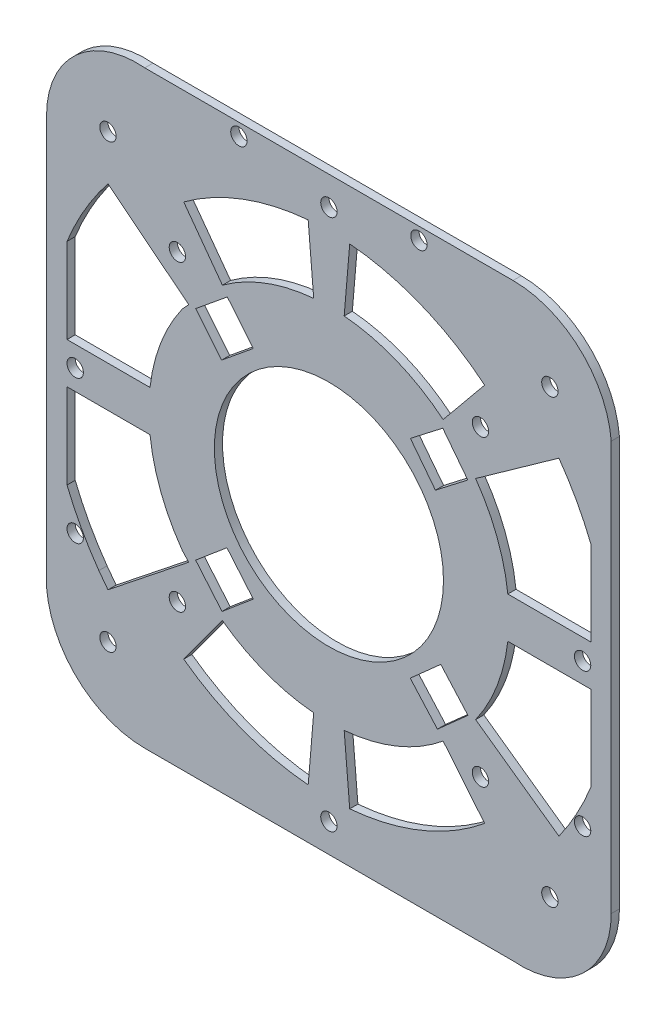
SolidWorks part; units mm, degrees
ref_plane "Front Plane" through (0, 0, 0) normal (0, 0, 1) x (1, 0, 0)
ref_plane "Top Plane" through (0, 0, 0) normal (0, 1, 0) x (1, 0, 0)
ref_plane "Right Plane" through (0, 0, 0) normal (1, 0, 0) x (0, 0, -1)
sketch "Sketch1" plane through (0, 0, 0) normal (0, 0, 1) x (1, 0, 0)
  line L1 (69, -50) -> (-69, -50)
  line L2 (69, -50) -> (69, 50)
  line L3 (69, 50) -> (-69, 50)
  line L4 (-69, -50) -> (-69, 50)
  line L5 (69, -50) -> (-69, 50) construction
  line L6 (69, 50) -> (-69, -50) construction
  line L7 (45, -72) -> (-45, -72)
  line L8 (45, -72) -> (45, 72)
  line L9 (45, 72) -> (-45, 72)
  line L10 (-45, -72) -> (-45, 72)
  line L11 (45, -72) -> (-45, 72) construction
  line L12 (45, 72) -> (-45, -72) construction
  arc A0 (-69, 50) -> (-45, 72) centre (-46.9167, 50) cw
  arc A1 (45, 72) -> (69, 50) centre (45, 47.9091) cw
  arc A2 (69, -50) -> (45, -72) centre (46.9167, -50) cw
  arc A3 (-45, -72) -> (-69, -50) centre (-45, -47.9091) cw
  point P0 (0, 0)
  point P6 (0, 0)
extrude "Boss-Extrude1" add sketch "Sketch1" along normal blind 2 contours L10 L1 L8 L3 | L10 L3 L8 L9 | L8 L1 L2 L3 | A1 L8 L3 | A2 L1 L8 | L10 L7 L8 L1 | A3 L10 L1 | L1 L10 L3 L4 | A0 L3 L10
sketch "Sketch2" plane through (0, 0, 2) normal (0, 0, 1) x (1, 0, 0)
  line L0 (-69, 0) -> (-64, 0)
  line L1 (69, 0) -> (64, 0)
  line L2 (-69, -50) -> (-69, 50) construction
  line L3 (64, 0) -> (64, 25.7876)
  line L4 (64, 25.7876) -> (64, -25.7876)
  line L5 (64, -25.7876) -> (-64, -25.7876)
  line L6 (-64, -25.7876) -> (-64, 25.7876)
  line L7 (-64, 25.7876) -> (64, 25.7876)
  line L8 (0, 60) -> (5.0847, 60)
  line L9 (0, 60) -> (-5.0847, 60)
  line L10 (-5.0847, 60) -> (-5.0847, 43.715)
  line L11 (-5.0847, 43.715) -> (5.0847, 43.715)
  line L12 (5.0847, 43.715) -> (5.0847, 60)
  line L13 (5.0847, 59.7842) -> (38.0593, 46.3842)
  line L14 (38.0593, 46.3842) -> (0, 0)
  line L15 (0, 0) -> (5.0847, 59.7842)
  line L16 (-5.0847, 60) -> (-35.4831, 48.3834)
  line L17 (-35.4831, 48.3834) -> (0, 0)
  line L18 (-5.0847, 60) -> (0, 0)
  line L19 (-69, 0) -> (-56.2174, 40.0076)
  line L20 (-56.2174, 40.0076) -> (0, 0)
  line L21 (0, 0) -> (-64, 0)
  line L22 (0, 72) -> (0, -72)
  line L23 (45, 72) -> (-45, 72) construction
  line L24 (45, -72) -> (-45, -72) construction
  line L25 (0, 0) -> (69, 0)
  line L26 (-69, 0) -> (-56.2174, -40.0076)
  line L27 (-56.2174, -40.0076) -> (0, 0)
  line L28 (-5.0847, -60) -> (0, 0)
  line L29 (-35.4831, -48.3834) -> (0, 0)
  line L30 (-5.0847, -60) -> (-35.4831, -48.3834)
  line L31 (38.0593, -46.3842) -> (0, 0)
  line L32 (0, 0) -> (5.0847, -59.7842)
  line L33 (5.0847, -59.7842) -> (38.0593, -46.3842)
  line L34 (56.2174, -40.0076) -> (0, 0)
  line L35 (69, 0) -> (56.2174, -40.0076)
  line L36 (64, -25.7876) -> (64, 25.7876)
  line L37 (69, 0) -> (56.2174, 40.0076)
  line L38 (56.2174, 40.0076) -> (0, 0)
  line L40 (64, 5) -> (-64, 5)
  line L41 (64, 5) -> (64, -5)
  line L42 (64, -5) -> (-64, -5)
  line L43 (-64, 5) -> (-64, -5)
  line L44 (64, 5) -> (-64, -5) construction
  line L45 (64, -5) -> (-64, 5) construction
  circle A0 centre (0, 0) radius 60
  circle A1 centre (0, 0) radius 69
  circle A2 centre (0, 0) radius 44.0097
extrude "Cut-Extrude1" cut sketch "Sketch2" against normal blind 10 contours A2 L14 L13 L12 | L13 A0 | A2 L12 L15 | A2 L18 A0 L10 | A2 L10 A0 L16 L17 | L16 A0 | L19 A1 L7 | A0 L20 L19 L7 | L20 A0 L7 | A2 L20 L7 A0 L40 | A0 L7 L19 L6 L40 | A2 L42 A0 L5 L27 | A0 L42 L6 L26 L5 | L26 L6 L5 | L5 A1 L26 | A0 L5 L26 L27 | L5 A0 L27 | A2 L32 L33 L31 | A2 L29 L30 A0 L28 | L30 A0 | L33 A0 | A0 L34 L35 L5 | L34 A0 L5 | L35 A1 L5 | L4 L35 L5 | A0 L5 L35 L36 L42 | A2 L34 L5 A0 L42 | A0 L40 L36 L37 L7 | A0 L7 L37 L38 | L7 A0 L38 | A2 L40 A0 L7 L38 | L7 A1 L37 | L37 L36 L7
sketch "Sketch3" plane through (0, 0, 2) normal (0, 0, 1) x (1, 0, 0)
  line L0 (-64, 25.7876) -> (-64, 15.6492)
  line L1 (-64, 15.6492) -> (-60.7607, 25.7876)
  line L2 (-60.7607, 25.7876) -> (-64, 25.7876)
extrude "Cut-Extrude2" cut sketch "Sketch3" against normal blind 10
sketch "Sketch4" plane through (0, 0, 0) normal (0, 0, -1) x (-1, 0, 0)
  circle A0 centre (0, 0) radius 30
extrude "Cut-Extrude3" cut sketch "Sketch4" against normal blind 10
sketch "Sketch6" plane through (0, 0, 2) normal (0, 0, 1) x (1, 0, 0)
  line L0 (-56.2174, -40.0076) -> (56.2174, -40.0076)
  line L1 (56.2174, -40.0076) -> (56.2174, 40.0076)
  line L2 (56.2174, 40.0076) -> (-56.2174, 40.0076)
  line L3 (-56.2174, 40.0076) -> (-56.2174, -40.0076)
  line L4 (27.9163, -34.0226) -> (35.8567, -25.5177)
  line L5 (-26.0267, -35.489) -> (-34.2574, -27.2582)
  line L6 (0, 0) -> (-34.2574, -27.2582)
  line L7 (-34.2574, -27.2582) -> (-53.9933, -42.9619)
  line L8 (-53.9933, -42.9619) -> (-56.2174, -40.0076)
  line L9 (-35.8567, -25.5177) -> (-34.2574, -27.2582)
  line L10 (-69, 0) -> (69, 0)
  line L11 (-35.8567, 25.5177) -> (-34.2574, 27.2582)
  line L12 (-53.9933, 42.9619) -> (-56.2174, 40.0076)
  line L13 (-34.2574, 27.2582) -> (-53.9933, 42.9619)
  circle A0 centre (0, 0) radius 69
  line M9 (-56.2174, 40.0076) -> (-35.8567, 25.5177)
  line M37 (-35.8567, -25.5177) -> (-56.2174, -40.0076)
extrude "Cut-Extrude4" cut sketch "Sketch6" against normal blind 10 contours L9 L0 L7 M37 | L11 L13 L2 M9 | L8 L7 L0 | L2 L13 L12
sketch "Sketch7" plane through (0, 0, 2) normal (0, 0, 1) x (1, 0, 0)
  line L4 (-26.2247, 19.5306) -> (-18.4877, 25.8662)
  line L5 (-34.2574, 27.2582) -> (-26.0267, 35.489)
  line L6 (-26.2247, 19.5306) -> (-32.5603, 27.2676)
  line L7 (38.0593, 46.3842) -> (27.9163, 34.0226) construction
  line L8 (27.9163, 34.0226) -> (35.8567, 25.5177)
  line L9 (-18.4877, 25.8662) -> (-24.8233, 33.6031)
  line L10 (35.8567, -25.5177) -> (27.9163, -34.0226)
  line L11 (-32.5603, 27.2676) -> (-24.8233, 33.6031)
  line L12 (-26.0267, -35.489) -> (-34.2574, -27.2582)
  line L15 (27.8278, 32.1554) -> (33.9427, 24.2429)
  line L16 (27.8278, 32.1554) -> (19.9153, 26.0405)
  line L17 (33.9427, 24.2429) -> (26.0302, 18.128)
  line L18 (19.9153, 26.0405) -> (26.0302, 18.128)
  line L21 (33.9883, -25.5491) -> (26.5216, -32.201)
  line L22 (33.9883, -25.5491) -> (27.3364, -18.0824)
  line L23 (26.5216, -32.201) -> (19.8697, -24.7343)
  line L24 (27.3364, -18.0824) -> (19.8697, -24.7343)
  line L27 (-26.1267, -33.6122) -> (-32.5693, -25.9642)
  line L28 (-26.1267, -33.6122) -> (-18.4787, -27.1696)
  line L29 (-32.5693, -25.9642) -> (-24.9213, -19.5215)
  line L30 (-18.4787, -27.1696) -> (-24.9213, -19.5215)
  arc A4 (27.9163, 34.0226) -> (3.7296, 43.8514) centre (0, 0) ccw construction
extrude "Cut-Extrude5" cut sketch "Sketch7" against normal blind 10 contours L11 L6 L4 L9 | L16 L18 L17 L15 | L22 L24 L23 L21 | L28 L30 L29 L27
sketch "Sketch8" plane through (0, 0, 2) normal (0, 0, 1) x (1, 0, 0)
  circle A0 centre (0, 0) radius 28
  circle A1 centre (0, 0) radius 30
extrude "Boss-Extrude3" add sketch "Sketch8" against normal blind 2
sketch "Sketch9" plane through (0, 0, 2) normal (0, 0, 1) x (1, 0, 0)
  line L5 (0, 29.15) -> (13, 29.15)
  line L6 (13, 29.15) -> (0, 29.15)
  line L7 (0, 29.15) -> (-13, 29.15)
  line L17 (61.2788, 65.6678) -> (62.0503, 65.0424)
  line L31 (-54, -54) -> (54, 54) construction
  line L34 (37.0294, -37.0294) -> (-37.0294, 37.0294) construction
  line L35 (37.0294, 37.0294) -> (-37.0294, -37.0294) construction
  circle A0 centre (-22, 69) radius 2
  circle A1 centre (22, 69) radius 2
  circle A2 centre (13, 29.15) radius 2
  circle A3 centre (-13, 29.15) radius 2
  circle A4 centre (62, -36.85) radius 2
  circle A5 centre (-62, -36.85) radius 2
  circle A6 centre (0, -36.85) radius 2
  circle A7 centre (0, 65) radius 2
  circle A8 centre (62, 0) radius 2
  circle A9 centre (-62, 0) radius 2
  circle A10 centre (0, -65) radius 2
  arc A11 (69, 50) -> (45, 72) centre (45, 47.9091) ccw construction
  circle A12 centre (-54, 54) radius 2
  circle A13 centre (54, 54) radius 2
  circle A14 centre (54, -54) radius 2
  circle A15 centre (-54, -54) radius 2
  circle A16 centre (-37.0294, 37.0294) radius 2
  circle A17 centre (37.0294, 37.0294) radius 2
  circle A18 centre (37.0294, -37.0294) radius 2
  circle A19 centre (-37.0294, -37.0294) radius 2
extrude "Cut-Extrude6" cut sketch "Sketch9" against normal blind 10
sketch "Sketch10" plane through (0, 0, 2) normal (0, 0, 1) x (1, 0, 0)
  circle A0 centre (62, -36.85) radius 2
  circle A1 centre (-62, -36.85) radius 2
  circle A2 centre (13, 29.15) radius 2
  circle A3 centre (-13, 29.15) radius 2
  circle A4 centre (0, -36.85) radius 2
extrude "Boss-Extrude4" add sketch "Sketch10" against normal up to surface (2 mm away) up to face at (39.0294, -37.0294, 0)
sketch "Sketch11" plane through (0, 0, 2) normal (0, 0, 1) x (1, 0, 0)
  line L0 (-22, 69) -> (22, 69)
  line L1 (22, 69) -> (0, 69)
  line L2 (0, 69) -> (0, -36)
  line L3 (0, -36) -> (62, -36)
  line L4 (0, -36) -> (-62, -36)
  circle A0 centre (-62, -36) radius 2
  circle A1 centre (62, -36) radius 2
extrude "Cut-Extrude7" cut sketch "Sketch11" against normal blind 10
sketch "Sketch12" plane through (0, 0, 2) normal (0, 0, 1) x (1, 0, 0)
  line L0 (-22, 69) -> (22, 69)
  line L1 (22, 69) -> (0, 69)
  line L2 (0, 69) -> (0, -35)
  line L3 (0, -35) -> (62, -36)
  circle A1 centre (62, -36) radius 2
  circle A2 centre (-62, -36) radius 2
extrude "Boss-Extrude5" add sketch "Sketch12" against normal up to surface (2 mm away)
sketch "Sketch13" plane through (0, 0, 2) normal (0, 0, 1) x (1, 0, 0)
  line L0 (-22, 69) -> (22, 69)
  line L1 (0, 69) -> (0, -35)
  line L2 (0, -35) -> (62, -35)
  line L3 (0, -35) -> (-62, -35)
  circle A0 centre (62, -35) radius 2
  circle A1 centre (-62, -35) radius 2
extrude "Cut-Extrude8" cut sketch "Sketch13" against normal blind 5
